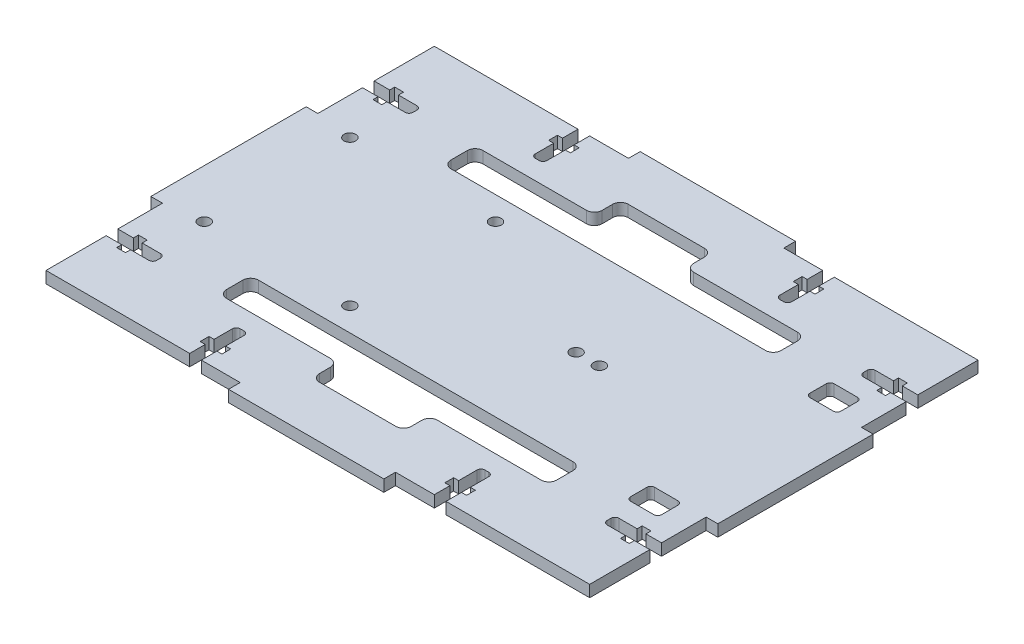
SolidWorks part; units mm, degrees
material "Acrylic (Medium-high impact)"
ref_plane "Plano frontal" through (0, 0, 0) normal (0, 0, 1) x (1, 0, 0)
ref_plane "Plano superior" through (0, 0, 0) normal (0, 1, 0) x (1, 0, 0)
ref_plane "Plano direito" through (0, 0, 0) normal (1, 0, 0) x (0, 0, -1)
sketch "Esboço1" plane through (0, 0, 0) normal (0, 1, 0) x (1, 0, 0)
  line L1 (-70, -50) -> (70, -50)
  line L2 (-70, -50) -> (-70, 50)
  line L3 (-70, 50) -> (70, 50)
  line L4 (70, -50) -> (70, 50)
  line L5 (-70, -50) -> (70, 50) construction
  line L6 (-70, 50) -> (70, -50) construction
  point P0 (0, 0)
  dimension "D1" = 140
  dimension "D2" = 100
extrude "Ressalto-extrusão1" add sketch "Esboço1" along normal mid plane 3
sketch "Esboço4" plane through (0, 1.5, 0) normal (0, 1, 0) x (1, 0, 0)
  line L5 (-70, 50) -> (-70, -50) construction
  line L6 (-70, 20) -> (-73, 20)
  line L7 (-70, 20) -> (-70, -20)
  line L8 (-70, -20) -> (-73, -20)
  line L9 (-73, 20) -> (-73, -20)
  line L16 (-20, 50) -> (20, 50)
  line L17 (-20, 50) -> (-20, 53)
  line L18 (-20, 53) -> (20, 53)
  line L19 (20, 50) -> (20, 53)
  line L20 (70, 50) -> (-70, 50) construction
  line L21 (-1.65, 0) -> (1.65, 0) construction
  line L22 (20, -50) -> (20, -53)
  line L23 (-20, -53) -> (20, -53)
  line L24 (-20, -50) -> (-20, -53)
  line L25 (-20, -50) -> (20, -50)
  line L26 (0, -1.65) -> (0, 1.65) construction
  line L27 (73, 20) -> (73, -20)
  line L28 (70, -20) -> (73, -20)
  line L29 (70, 20) -> (70, -20)
  line L30 (70, 20) -> (73, 20)
  point P14 (-73, 0)
  point P28 (0, 53)
  dimension "D3" = 3
  dimension "D4" = 40
extrude "Ressalto-extrusão2" add sketch "Esboço4" against normal through all
sketch "Esboço2" plane through (0, 1.5, 0) normal (0, 1, 0) x (1, 0, 0)
  line L0 (-33, -43.73) -> (-33, -39)
  line L13 (-30, -46) -> (-28.7, -46)
  line L14 (-30, -43.73) -> (-30, -39)
  line L27 (-70, -50) -> (-20, -50) construction
  line L28 (-33, -50) -> (-30, -50)
  line L29 (-33, -50) -> (-33, -46)
  line L30 (-32, -38) -> (-31, -38)
  line L31 (-30, -50) -> (-30, -46)
  line L33 (-30, -43.73) -> (-28.7, -43.73)
  line L34 (-34.3, -46) -> (-33, -46)
  line L35 (-34.3, -46) -> (-34.3, -43.73)
  line L36 (-34.3, -43.73) -> (-33, -43.73)
  line L37 (-28.7, -46) -> (-28.7, -43.73)
  line L38 (-20, -50) -> (-20, -53) construction
  line L51 (-1.65, 0) -> (1.65, 0) construction
  line L52 (-28.7, 46) -> (-28.7, 43.73)
  line L53 (-34.3, 43.73) -> (-33, 43.73)
  line L54 (-34.3, 46) -> (-34.3, 43.73)
  line L55 (-34.3, 46) -> (-33, 46)
  line L56 (-30, 43.73) -> (-28.7, 43.73)
  line L57 (-30, 50) -> (-30, 46)
  line L58 (-32, 38) -> (-31, 38)
  line L59 (-33, 50) -> (-33, 46)
  line L60 (-33, 50) -> (-30, 50)
  line L61 (-30, 43.73) -> (-30, 39)
  line L62 (-30, 46) -> (-28.7, 46)
  line L63 (-33, 43.73) -> (-33, 39)
  line L64 (0, -1.65) -> (0, 1.65) construction
  line L65 (33, 43.73) -> (33, 39)
  line L66 (30, 46) -> (28.7, 46)
  line L67 (30, 43.73) -> (30, 39)
  line L68 (33, 50) -> (30, 50)
  line L69 (33, 50) -> (33, 46)
  line L70 (32, 38) -> (31, 38)
  line L71 (30, 50) -> (30, 46)
  line L72 (30, 43.73) -> (28.7, 43.73)
  line L73 (34.3, 46) -> (33, 46)
  line L74 (34.3, 46) -> (34.3, 43.73)
  line L75 (34.3, 43.73) -> (33, 43.73)
  line L76 (28.7, 46) -> (28.7, 43.73)
  line L77 (28.7, -46) -> (28.7, -43.73)
  line L78 (34.3, -43.73) -> (33, -43.73)
  line L79 (34.3, -46) -> (34.3, -43.73)
  line L80 (34.3, -46) -> (33, -46)
  line L81 (30, -43.73) -> (28.7, -43.73)
  line L82 (30, -50) -> (30, -46)
  line L83 (32, -38) -> (31, -38)
  line L84 (33, -50) -> (33, -46)
  line L85 (33, -50) -> (30, -50)
  line L86 (30, -43.73) -> (30, -39)
  line L87 (30, -46) -> (28.7, -46)
  line L88 (33, -43.73) -> (33, -39)
  arc A0 (-31, -38) -> (-30, -39) centre (-31, -39) cw
  arc A1 (-33, -39) -> (-32, -38) centre (-32, -39) cw
  arc A2 (-33, 39) -> (-32, 38) centre (-32, 39) ccw
  arc A3 (-31, 38) -> (-30, 39) centre (-31, 39) ccw
  arc A4 (31, 38) -> (30, 39) centre (31, 39) cw
  arc A5 (33, 39) -> (32, 38) centre (32, 39) cw
  arc A6 (33, -39) -> (32, -38) centre (32, -39) ccw
  arc A7 (31, -38) -> (30, -39) centre (31, -39) ccw
  point P20 (-33, -38)
  point P39 (-33, 38)
  point P74 (33, 38)
  point P75 (33, -38)
  dimension "D8" = 1
  dimension "D1" = 10
  dimension "D2" = 3
  dimension "D3" = 12
  dimension "D4" = 4
  dimension "D5" = 1.3
  dimension "D6" = 2.27
  dimension "D7" = 1.3
extrude "Corte-extrusão1" cut sketch "Esboço2" against normal through all
sketch "Esboço7" plane through (0, 1.5, 0) normal (0, 1, 0) x (1, 0, 0)
  line L0 (-70, -20) -> (-70, -50) construction
  line L1 (-70, -31.5) -> (-66, -31.5)
  line L2 (-70, -31.5) -> (-70, -34.5)
  line L3 (-70, -34.5) -> (-66, -34.5)
  line L4 (-58, -32.5) -> (-58, -33.5)
  line L6 (-66, -30.2) -> (-63.73, -30.2)
  line L7 (-66, -30.2) -> (-66, -31.5)
  line L8 (-66, -35.8) -> (-63.73, -35.8)
  line L9 (-63.73, -30.2) -> (-63.73, -31.5)
  line L10 (-63.73, -31.5) -> (-59, -31.5)
  line L11 (-63.73, -34.5) -> (-59, -34.5)
  line L12 (-63.73, -34.5) -> (-63.73, -35.8)
  line L13 (-66, -34.5) -> (-66, -35.8)
  line L14 (-73, -20) -> (-70, -20) construction
  line L15 (0, -1.65) -> (0, 1.65) construction
  line L17 (66, -34.5) -> (66, -35.8)
  line L18 (63.73, -34.5) -> (63.73, -35.8)
  line L19 (63.73, -34.5) -> (59, -34.5)
  line L20 (63.73, -31.5) -> (59, -31.5)
  line L21 (63.73, -30.2) -> (63.73, -31.5)
  line L22 (66, -35.8) -> (63.73, -35.8)
  line L23 (66, -30.2) -> (66, -31.5)
  line L24 (66, -30.2) -> (63.73, -30.2)
  line L25 (58, -32.5) -> (58, -33.5)
  line L26 (70, -34.5) -> (66, -34.5)
  line L27 (70, -31.5) -> (70, -34.5)
  line L28 (70, -31.5) -> (66, -31.5)
  line L29 (-1.65, 0) -> (1.65, 0) construction
  line L32 (70, 31.5) -> (66, 31.5)
  line L33 (70, 31.5) -> (70, 34.5)
  line L34 (70, 34.5) -> (66, 34.5)
  line L35 (58, 32.5) -> (58, 33.5)
  line L36 (66, 30.2) -> (63.73, 30.2)
  line L37 (66, 30.2) -> (66, 31.5)
  line L38 (66, 35.8) -> (63.73, 35.8)
  line L39 (63.73, 30.2) -> (63.73, 31.5)
  line L40 (63.73, 31.5) -> (59, 31.5)
  line L41 (63.73, 34.5) -> (59, 34.5)
  line L42 (63.73, 34.5) -> (63.73, 35.8)
  line L43 (66, 34.5) -> (66, 35.8)
  line L44 (-66, 34.5) -> (-66, 35.8)
  line L45 (-63.73, 34.5) -> (-63.73, 35.8)
  line L46 (-63.73, 34.5) -> (-59, 34.5)
  line L47 (-63.73, 31.5) -> (-59, 31.5)
  line L48 (-63.73, 30.2) -> (-63.73, 31.5)
  line L49 (-66, 35.8) -> (-63.73, 35.8)
  line L50 (-66, 30.2) -> (-66, 31.5)
  line L51 (-66, 30.2) -> (-63.73, 30.2)
  line L52 (-58, 32.5) -> (-58, 33.5)
  line L53 (-70, 34.5) -> (-66, 34.5)
  line L54 (-70, 31.5) -> (-70, 34.5)
  line L55 (-70, 31.5) -> (-66, 31.5)
  arc A0 (59, -34.5) -> (58, -33.5) centre (59, -33.5) cw
  arc A1 (59, -31.5) -> (58, -32.5) centre (59, -32.5) ccw
  arc A2 (58, 32.5) -> (59, 31.5) centre (59, 32.5) ccw
  arc A3 (58, 33.5) -> (59, 34.5) centre (59, 33.5) cw
  arc A4 (-59, 34.5) -> (-58, 33.5) centre (-59, 33.5) cw
  arc A5 (-59, 31.5) -> (-58, 32.5) centre (-59, 32.5) ccw
  arc A6 (-59, -31.5) -> (-58, -32.5) centre (-59, -32.5) cw
  arc A7 (-59, -34.5) -> (-58, -33.5) centre (-59, -33.5) ccw
  point P22 (58, -34.5)
  point P68 (58, -31.5)
  point P71 (58, 31.5)
  point P74 (58, 34.5)
  point P77 (-58, 34.5)
  point P80 (-58, 31.5)
  point P83 (-58, -31.5)
  point P86 (-58, -34.5)
  dimension "D8" = 1
  dimension "D1" = 3
  dimension "D2" = 12
  dimension "D3" = 2.27
  dimension "D4" = 4
  dimension "D5" = 1.3
  dimension "D6" = 11.5
  dimension "D7" = 1.3
extrude "Corte-extrusão4" cut sketch "Esboço7" against normal through all
sketch "Esboço13" plane through (0, -1.5, 0) normal (0, -1, 0) x (-1, 0, 0)
  line L0 (60.5, 18.75) -> (60.5, -18.75) construction
  line L2 (51.5, 50) -> (51.5, -50) construction
  line L3 (33, 50) -> (70, 50) construction
  line L4 (70, -50) -> (33, -50) construction
  line L6 (70, 31.5) -> (70, 20) construction
  circle A0 centre (60.5, -18.75) radius 1.5
  circle A1 centre (23, -18.75) radius 1.5
  circle A2 centre (60.5, 18.75) radius 1.5
  circle A3 centre (23, 18.75) radius 1.5
  point P10 (60.5, 0)
  dimension "D1" = 3
  dimension "D2" = 8
  dimension "D3" = 37.5
  dimension "D5" = 37.5
  dimension "D6" = 100
extrude "Corte-extrusão8" cut sketch "Esboço13" against normal through all both and the other way through all
sketch "Sketch3" plane through (0, 1.5, 0) normal (0, 1, 0) x (1, 0, 0)
  circle A0 centre (16.5, 0) radius 1.5
  circle A1 centre (22.5, 0) radius 1.5
  dimension "D1" = 3
  dimension "D2" = 3
  dimension "D3" = 16.5
extrude "Cut-Extrude2" cut sketch "Sketch3" against normal through all both and the other way through all
sketch "Sketch4" plane through (0, 0, 0) normal (0, 1, 0) x (1, 0, 0)
  line L0 (-1.65, 0) -> (1.65, 0) construction
  line L10 (-40.5, 33) -> (-13.8, 33)
  line L17 (-42.5, 31) -> (-42.5, 26.8)
  line L18 (-40.5, 24.8) -> (40.5, 24.8)
  line L19 (42.5, 31) -> (42.5, 26.8)
  line L21 (-11.8, 35) -> (-11.8, 37.73)
  line L22 (-9.8, 39.73) -> (9.8, 39.73)
  line L23 (11.8, 35) -> (11.8, 37.73)
  line L24 (13.8, -33) -> (40.5, -33)
  line L25 (13.8, 33) -> (40.5, 33)
  line L26 (-32, 38) -> (-31, 38) construction
  line L27 (-30, 43.73) -> (-28.7, 43.73) construction
  line L28 (11.8, -35) -> (11.8, -37.73)
  line L29 (-9.8, -39.73) -> (9.8, -39.73)
  line L30 (-11.8, -35) -> (-11.8, -37.73)
  line L31 (42.5, -31) -> (42.5, -26.8)
  line L32 (-40.5, -24.8) -> (40.5, -24.8)
  line L33 (-42.5, -31) -> (-42.5, -26.8)
  line L34 (-40.5, -33) -> (-13.8, -33)
  line L41 (73, 20) -> (70, 20) construction
  line L42 (56.73, 26.2) -> (62.73, 26.2)
  line L43 (55.73, 25.2) -> (55.73, 21)
  line L44 (56.73, 20) -> (62.73, 20)
  line L45 (63.73, 25.2) -> (63.73, 21)
  line L47 (63.73, 31.5) -> (63.73, 30.2) construction
  line L48 (63.73, 30.2) -> (66, 30.2) construction
  line L49 (63.73, -25.2) -> (63.73, -21)
  line L50 (56.73, -20) -> (62.73, -20)
  line L51 (55.73, -25.2) -> (55.73, -21)
  line L52 (56.73, -26.2) -> (62.73, -26.2)
  circle A0 centre (-23, 18.75) radius 1.5 construction
  arc A1 (13.8, 33) -> (11.8, 35) centre (13.8, 35) cw
  arc A2 (-13.8, 33) -> (-11.8, 35) centre (-13.8, 35) ccw
  arc A3 (9.8, 39.73) -> (11.8, 37.73) centre (9.8, 37.73) cw
  arc A4 (-11.8, 37.73) -> (-9.8, 39.73) centre (-9.8, 37.73) cw
  arc A5 (40.5, 24.8) -> (42.5, 26.8) centre (40.5, 26.8) ccw
  arc A6 (40.5, 33) -> (42.5, 31) centre (40.5, 31) cw
  arc A7 (-42.5, 26.8) -> (-40.5, 24.8) centre (-40.5, 26.8) ccw
  arc A8 (-40.5, 33) -> (-42.5, 31) centre (-40.5, 31) ccw
  arc A9 (-40.5, -33) -> (-42.5, -31) centre (-40.5, -31) cw
  arc A10 (-42.5, -26.8) -> (-40.5, -24.8) centre (-40.5, -26.8) cw
  arc A11 (40.5, -33) -> (42.5, -31) centre (40.5, -31) ccw
  arc A12 (40.5, -24.8) -> (42.5, -26.8) centre (40.5, -26.8) cw
  arc A13 (-11.8, -37.73) -> (-9.8, -39.73) centre (-9.8, -37.73) ccw
  arc A14 (9.8, -39.73) -> (11.8, -37.73) centre (9.8, -37.73) ccw
  arc A15 (-13.8, -33) -> (-11.8, -35) centre (-13.8, -35) cw
  arc A16 (13.8, -33) -> (11.8, -35) centre (13.8, -35) ccw
  arc A21 (62.73, 26.2) -> (63.73, 25.2) centre (62.73, 25.2) cw
  arc A22 (62.73, 20) -> (63.73, 21) centre (62.73, 21) ccw
  arc A23 (55.73, 21) -> (56.73, 20) centre (56.73, 21) ccw
  arc A24 (56.73, 26.2) -> (55.73, 25.2) centre (56.73, 25.2) ccw
  arc A25 (56.73, -26.2) -> (55.73, -25.2) centre (56.73, -25.2) cw
  arc A26 (55.73, -21) -> (56.73, -20) centre (56.73, -21) cw
  arc A27 (62.73, -20) -> (63.73, -21) centre (62.73, -21) cw
  arc A28 (62.73, -26.2) -> (63.73, -25.2) centre (62.73, -25.2) ccw
  point P4 (0, 24.8)
  point P11 (0, 39.73)
  point P26 (42.5, 24.8)
  point P31 (-42.5, 24.8)
  point P61 (-42.5, -24.8)
  point P62 (42.5, -24.8)
  point P75 (63.73, 26.2)
  point P82 (55.73, 26.2)
  point P95 (55.73, -26.2)
  point P96 (63.73, -26.2)
  dimension "D4" = 4.55
  dimension "D1" = 85
  dimension "D3" = 5
  dimension "D6" = 23.6
  dimension "D7" = 4
  dimension "D2" = 2
  dimension "D5" = 2
  dimension "D10" = 1
  dimension "D8" = 4
  dimension "D9" = 8
extrude "Cut-Extrude3" cut sketch "Sketch4" against normal through all both and the other way through all
